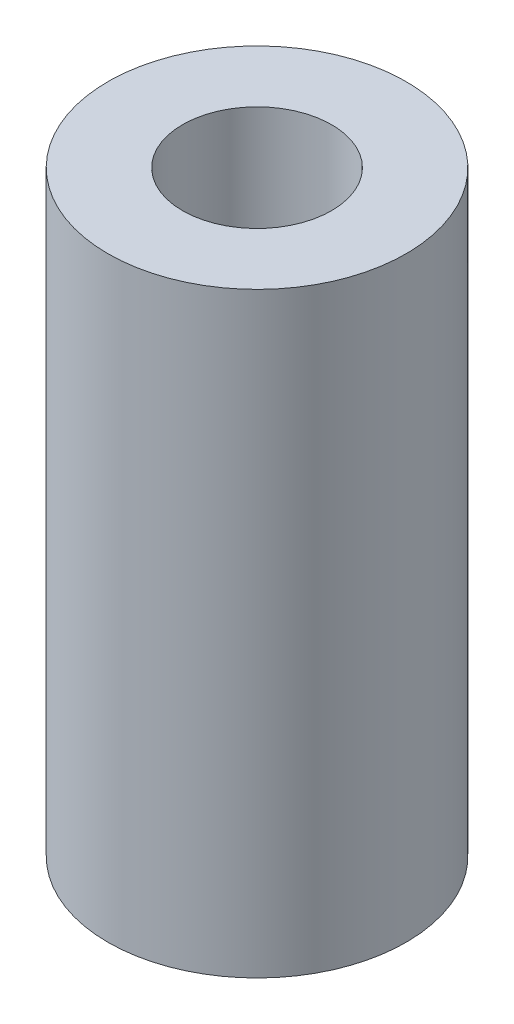
SolidWorks part; units mm, degrees
ref_plane "Front Plane" through (0, 0, 0) normal (0, 0, 1) x (1, 0, 0)
ref_plane "Top Plane" through (0, 0, 0) normal (0, 1, 0) x (1, 0, 0)
ref_plane "Right Plane" through (0, 0, 0) normal (1, 0, 0) x (0, 0, -1)
sketch "Sketch1" plane through (0, 0, 0) normal (0, 1, 0) x (1, 0, 0)
  circle A0 centre (0, 0) radius 3.175
  circle A1 centre (0, 0) radius 1.5875
  dimension "D1" = 3.175
  dimension "D2" = 6.35
extrude "Boss-Extrude1" add sketch "Sketch1" along normal blind 12.7
